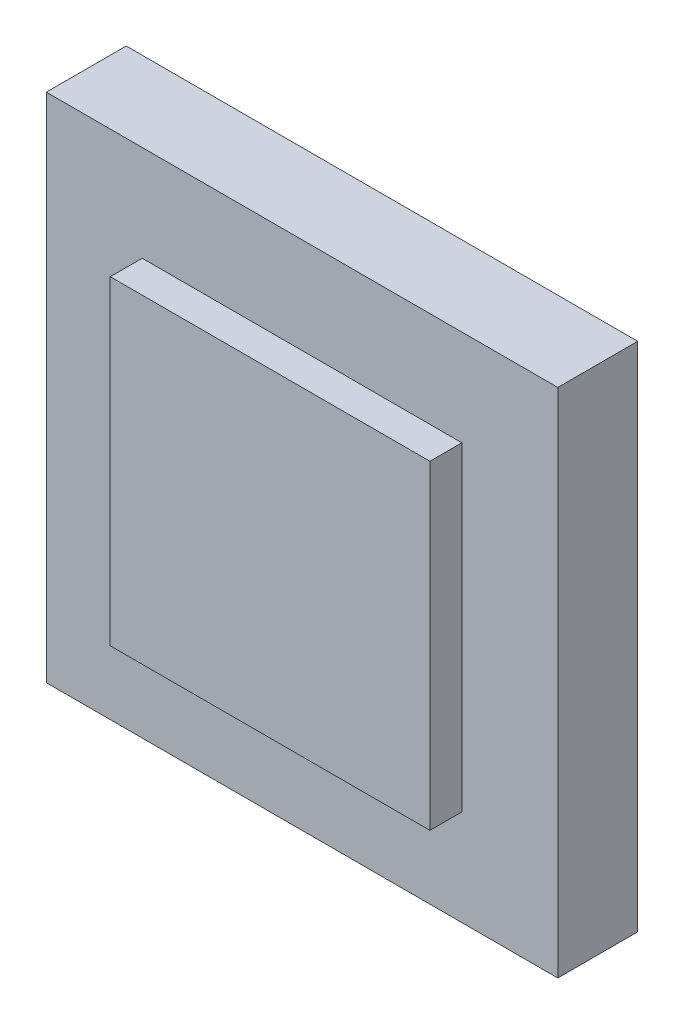
SolidWorks part; units mm, degrees
ref_plane "Front Plane" through (0, 0, 0) normal (0, 0, 1) x (1, 0, 0)
ref_plane "Top Plane" through (0, 0, 0) normal (0, 1, 0) x (1, 0, 0)
ref_plane "Right Plane" through (0, 0, 0) normal (1, 0, 0) x (0, 0, -1)
sketch "Sketch2" plane through (0, 0, 0) normal (0, 0, 1) x (1, 0, 0)
  line L1 (-203.2, 203.2) -> (203.2, 203.2)
  line L2 (-203.2, 203.2) -> (-203.2, -203.2)
  line L3 (-203.2, -203.2) -> (203.2, -203.2)
  line L4 (203.2, 203.2) -> (203.2, -203.2)
  line L5 (-203.2, 203.2) -> (203.2, -203.2) construction
  line L6 (-203.2, -203.2) -> (203.2, 203.2) construction
  point P0 (0, 0)
  dimension "D1" = 406.4
  dimension "D2" = 406.4
extrude "Boss-Extrude1" add sketch "Sketch2" along normal blind 63.5
sketch "Sketch3" plane through (0, 0, 63.5) normal (0, 0, 1) x (1, 0, 0)
  line L1 (-127, 127) -> (127, 127)
  line L2 (-127, 127) -> (-127, -127)
  line L3 (-127, -127) -> (127, -127)
  line L4 (127, 127) -> (127, -127)
  line L5 (-127, 127) -> (127, -127) construction
  line L6 (-127, -127) -> (127, 127) construction
  point P0 (0, 0)
  dimension "D1" = 254
  dimension "D2" = 254
extrude "Boss-Extrude2" add sketch "Sketch3" along normal blind 25.4
